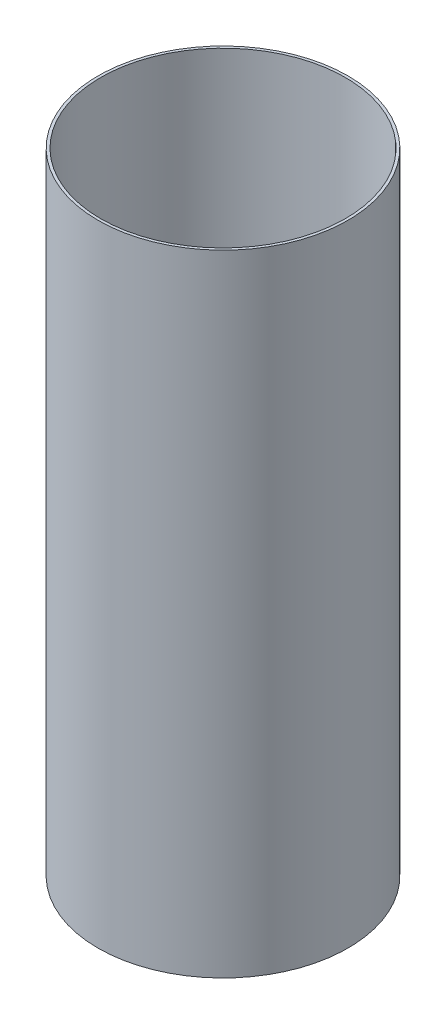
SolidWorks part; units mm, degrees
material "CF (correct density)"
ref_plane "Front Plane" through (0, 0, 0) normal (0, 0, 1) x (1, 0, 0)
ref_plane "Top Plane" through (0, 0, 0) normal (0, 1, 0) x (1, 0, 0)
ref_plane "Right Plane" through (0, 0, 0) normal (1, 0, 0) x (0, 0, -1)
sketch "Sketch1" plane through (0, 0, 0) normal (0, 1, 0) x (1, 0, 0)
  circle A0 centre (0, 0) radius 76.4286
  circle A1 centre (0, 0) radius 78.105
  dimension "D1" = 152.8572
  dimension "D2" = 1.6764
extrude "Boss-Extrude1" add sketch "Sketch1" along normal blind 393.7
